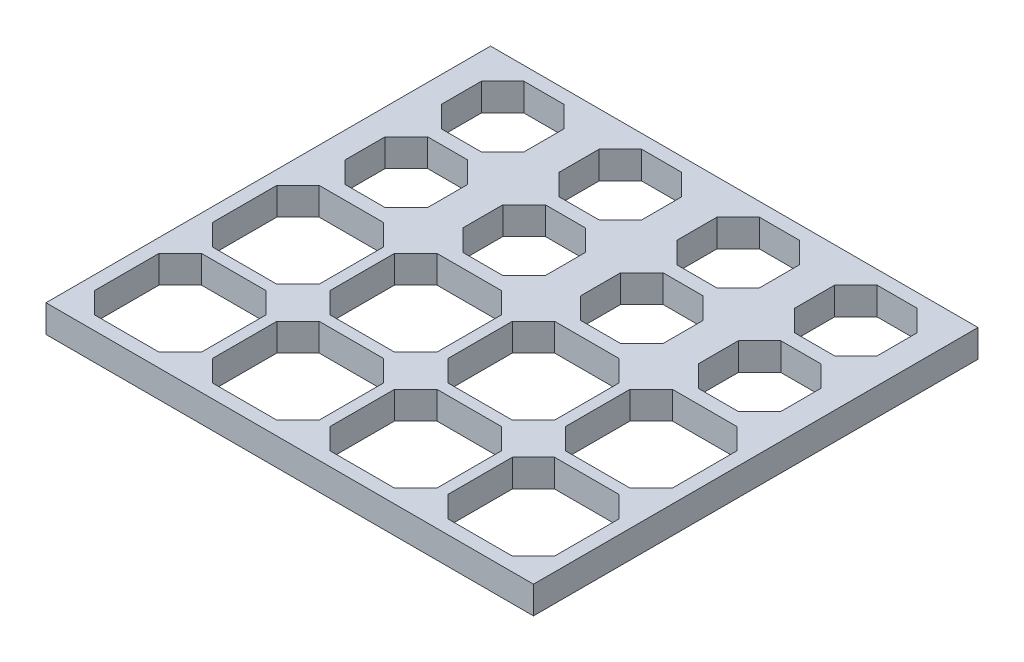
SolidWorks part; units mm, degrees
ref_plane "Front Plane" through (0, 0, 0) normal (0, 0, 1) x (1, 0, 0)
ref_plane "Top Plane" through (0, 0, 0) normal (0, 1, 0) x (1, 0, 0)
ref_plane "Right Plane" through (0, 0, 0) normal (1, 0, 0) x (0, 0, -1)
sketch "Sketch1" plane through (0, 0, 0) normal (0, 1, 0) x (1, 0, 0)
  line L0 (5, 36.1127) -> (5, 12.6873)
  line L1 (0, 0) -> (177.2, 0)
  line L2 (0, 0) -> (0, 161.6)
  line L3 (0, 161.6) -> (177.2, 161.6)
  line L4 (177.2, 0) -> (177.2, 161.6)
  line L5 (5, 12.6873) -> (12.6873, 5)
  line L6 (12.6873, 5) -> (36.1127, 5)
  line L7 (36.1127, 5) -> (43.8, 12.6873)
  line L8 (43.8, 12.6873) -> (43.8, 36.1127)
  line L9 (43.8, 36.1127) -> (36.1127, 43.8)
  line L10 (36.1127, 43.8) -> (12.6873, 43.8)
  line L11 (12.6873, 43.8) -> (5, 36.1127)
  line L12 (55.4873, 43.8) -> (47.8, 36.1127)
  line L13 (47.8, 36.1127) -> (47.8, 12.6873)
  line L14 (47.8, 12.6873) -> (55.4873, 5)
  line L15 (55.4873, 5) -> (78.9127, 5)
  line L16 (78.9127, 5) -> (86.6, 12.6873)
  line L17 (86.6, 12.6873) -> (86.6, 36.1127)
  line L18 (86.6, 36.1127) -> (78.9127, 43.8)
  line L19 (78.9127, 43.8) -> (55.4873, 43.8)
  line L20 (98.2873, 43.8) -> (90.6, 36.1127)
  line L21 (90.6, 36.1127) -> (90.6, 12.6873)
  line L22 (90.6, 12.6873) -> (98.2873, 5)
  line L23 (98.2873, 5) -> (121.7127, 5)
  line L24 (121.7127, 5) -> (129.4, 12.6873)
  line L25 (129.4, 12.6873) -> (129.4, 36.1127)
  line L26 (129.4, 36.1127) -> (121.7127, 43.8)
  line L27 (121.7127, 43.8) -> (98.2873, 43.8)
  line L28 (141.0873, 43.8) -> (133.4, 36.1127)
  line L29 (133.4, 36.1127) -> (133.4, 12.6873)
  line L30 (133.4, 12.6873) -> (141.0873, 5)
  line L31 (141.0873, 5) -> (164.5127, 5)
  line L32 (164.5127, 5) -> (172.2, 12.6873)
  line L33 (172.2, 12.6873) -> (172.2, 36.1127)
  line L34 (172.2, 36.1127) -> (164.5127, 43.8)
  line L35 (164.5127, 43.8) -> (141.0873, 43.8)
  line L36 (55.4873, 86.6) -> (47.8, 78.9127)
  line L37 (47.8, 78.9127) -> (47.8, 55.4873)
  line L38 (47.8, 55.4873) -> (55.4873, 47.8)
  line L39 (55.4873, 47.8) -> (78.9127, 47.8)
  line L40 (78.9127, 47.8) -> (86.6, 55.4873)
  line L41 (86.6, 55.4873) -> (86.6, 78.9127)
  line L42 (86.6, 78.9127) -> (78.9127, 86.6)
  line L43 (78.9127, 86.6) -> (55.4873, 86.6)
  line L44 (98.2873, 86.6) -> (90.6, 78.9127)
  line L45 (90.6, 78.9127) -> (90.6, 55.4873)
  line L46 (90.6, 55.4873) -> (98.2873, 47.8)
  line L47 (98.2873, 47.8) -> (121.7127, 47.8)
  line L48 (121.7127, 47.8) -> (129.4, 55.4873)
  line L49 (129.4, 55.4873) -> (129.4, 78.9127)
  line L50 (129.4, 78.9127) -> (121.7127, 86.6)
  line L51 (121.7127, 86.6) -> (98.2873, 86.6)
  line L52 (141.0873, 86.6) -> (133.4, 78.9127)
  line L53 (133.4, 78.9127) -> (133.4, 55.4873)
  line L54 (133.4, 55.4873) -> (141.0873, 47.8)
  line L55 (141.0873, 47.8) -> (164.5127, 47.8)
  line L56 (164.5127, 47.8) -> (172.2, 55.4873)
  line L57 (172.2, 55.4873) -> (172.2, 78.9127)
  line L58 (172.2, 78.9127) -> (164.5127, 86.6)
  line L59 (164.5127, 86.6) -> (141.0873, 86.6)
  line L60 (12.6873, 86.6) -> (5, 78.9127)
  line L61 (5, 78.9127) -> (5, 55.4873)
  line L62 (5, 55.4873) -> (12.6873, 47.8)
  line L63 (12.6873, 47.8) -> (36.1127, 47.8)
  line L64 (36.1127, 47.8) -> (43.8, 55.4873)
  line L65 (43.8, 55.4873) -> (43.8, 78.9127)
  line L66 (43.8, 78.9127) -> (36.1127, 86.6)
  line L67 (36.1127, 86.6) -> (12.6873, 86.6)
  line L68 (9.4, 113.8739) -> (9.4, 99.3261)
  line L73 (9.4, 99.3261) -> (17.1261, 91.6)
  line L74 (17.1261, 91.6) -> (31.6739, 91.6)
  line L75 (31.6739, 91.6) -> (39.4, 99.3261)
  line L76 (39.4, 99.3261) -> (39.4, 113.8739)
  line L77 (39.4, 113.8739) -> (31.6739, 121.6)
  line L78 (31.6739, 121.6) -> (17.1261, 121.6)
  line L79 (17.1261, 121.6) -> (9.4, 113.8739)
  line L80 (129.4, 36.1127) -> (133.4, 36.1127) construction
  line L81 (141.0873, 43.8) -> (141.0873, 47.8) construction
  line L82 (24.4, 86.6) -> (24.4, 91.6) construction
  line L83 (52.2, 113.8739) -> (52.2, 99.3261)
  line L84 (52.2, 99.3261) -> (59.9261, 91.6)
  line L85 (59.9261, 91.6) -> (74.4739, 91.6)
  line L86 (74.4739, 91.6) -> (82.2, 99.3261)
  line L87 (82.2, 99.3261) -> (82.2, 113.8739)
  line L88 (82.2, 113.8739) -> (74.4739, 121.6)
  line L89 (74.4739, 121.6) -> (59.9261, 121.6)
  line L90 (59.9261, 121.6) -> (52.2, 113.8739)
  line L91 (95, 113.8739) -> (95, 99.3261)
  line L92 (95, 99.3261) -> (102.7261, 91.6)
  line L93 (102.7261, 91.6) -> (117.2739, 91.6)
  line L94 (117.2739, 91.6) -> (125, 99.3261)
  line L95 (125, 99.3261) -> (125, 113.8739)
  line L96 (125, 113.8739) -> (117.2739, 121.6)
  line L97 (117.2739, 121.6) -> (102.7261, 121.6)
  line L98 (102.7261, 121.6) -> (95, 113.8739)
  line L99 (137.8, 113.8739) -> (137.8, 99.3261)
  line L100 (137.8, 99.3261) -> (145.5261, 91.6)
  line L101 (145.5261, 91.6) -> (160.0739, 91.6)
  line L102 (160.0739, 91.6) -> (167.8, 99.3261)
  line L103 (167.8, 99.3261) -> (167.8, 113.8739)
  line L104 (167.8, 113.8739) -> (160.0739, 121.6)
  line L105 (160.0739, 121.6) -> (145.5261, 121.6)
  line L106 (145.5261, 121.6) -> (137.8, 113.8739)
  line L107 (52.2, 148.8739) -> (52.2, 134.3261)
  line L108 (52.2, 134.3261) -> (59.9261, 126.6)
  line L109 (59.9261, 126.6) -> (74.4739, 126.6)
  line L110 (74.4739, 126.6) -> (82.2, 134.3261)
  line L111 (82.2, 134.3261) -> (82.2, 148.8739)
  line L112 (82.2, 148.8739) -> (74.4739, 156.6)
  line L113 (74.4739, 156.6) -> (59.9261, 156.6)
  line L114 (59.9261, 156.6) -> (52.2, 148.8739)
  line L115 (95, 148.8739) -> (95, 134.3261)
  line L116 (95, 134.3261) -> (102.7261, 126.6)
  line L117 (102.7261, 126.6) -> (117.2739, 126.6)
  line L118 (117.2739, 126.6) -> (125, 134.3261)
  line L119 (125, 134.3261) -> (125, 148.8739)
  line L120 (125, 148.8739) -> (117.2739, 156.6)
  line L121 (117.2739, 156.6) -> (102.7261, 156.6)
  line L122 (102.7261, 156.6) -> (95, 148.8739)
  line L123 (137.8, 148.8739) -> (137.8, 134.3261)
  line L124 (137.8, 134.3261) -> (145.5261, 126.6)
  line L125 (145.5261, 126.6) -> (160.0739, 126.6)
  line L126 (160.0739, 126.6) -> (167.8, 134.3261)
  line L127 (167.8, 134.3261) -> (167.8, 148.8739)
  line L128 (167.8, 148.8739) -> (160.0739, 156.6)
  line L129 (160.0739, 156.6) -> (145.5261, 156.6)
  line L130 (145.5261, 156.6) -> (137.8, 148.8739)
  line L131 (9.4, 148.8739) -> (9.4, 134.3261)
  line L132 (9.4, 134.3261) -> (17.1261, 126.6)
  line L133 (17.1261, 126.6) -> (31.6739, 126.6)
  line L134 (31.6739, 126.6) -> (39.4, 134.3261)
  line L135 (39.4, 134.3261) -> (39.4, 148.8739)
  line L136 (39.4, 148.8739) -> (31.6739, 156.6)
  line L137 (31.6739, 156.6) -> (17.1261, 156.6)
  line L138 (17.1261, 156.6) -> (9.4, 148.8739)
  line L139 (152.8, 86.6) -> (152.8, 91.6) construction
  line L140 (137.8, 106.6) -> (125, 106.6) construction
  line L141 (152.8, 121.6) -> (152.8, 126.6) construction
  point P78 (35.5369, 117.7369)
  point P142 (180.2, 188.8234)
  point P143 (148.5133, 122.6)
  point P144 (0, 0)
  point P145 (39.4083, 100.3344)
  point P146 (119.2904, 92.6)
  dimension "D1" = 135
  dimension "D2" = 38.8
  dimension "D3" = 5
  dimension "D4" = 5
  dimension "D5" = 44
  dimension "D8" = 30
  dimension "D9" = 31.5
  dimension "D10" = 5
  dimension "D11" = 4
  dimension "D12" = 4
  dimension "D14" = 5
  dimension "D15" = 5
  dimension "D16" = 135
  dimension "D6" = 4
  dimension "D7" = 2
  dimension "D13" = 2
extrude "Boss-Extrude1" add sketch "Sketch1" along normal blind 10
